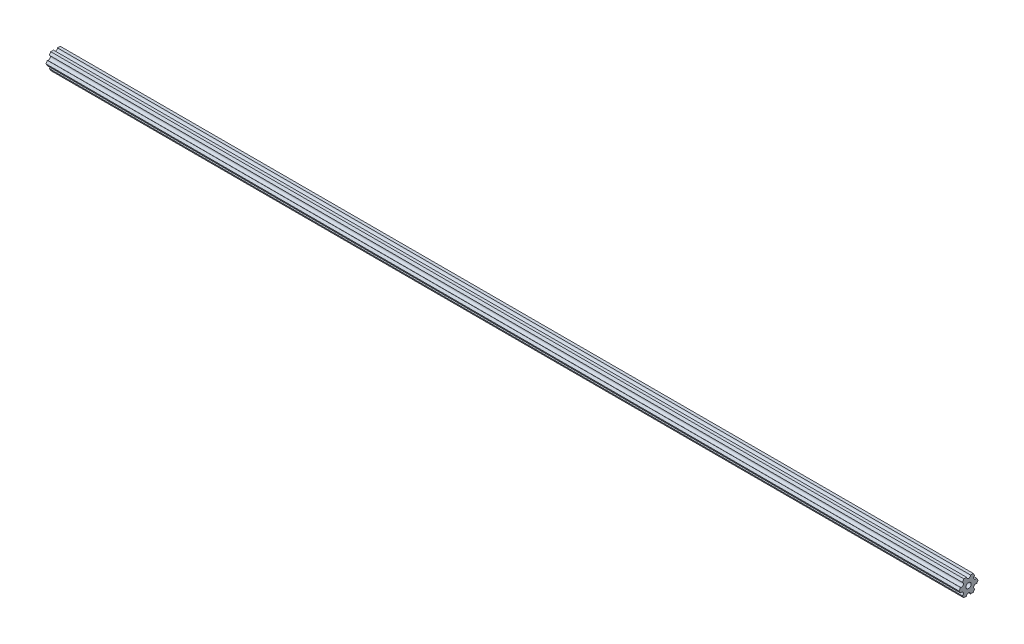
SolidWorks part; units mm, degrees
material "6061 Alloy"
ref_plane "Front Plane" through (0, 0, 0) normal (0, 0, 1) x (1, 0, 0)
ref_plane "Top Plane" through (0, 0, 0) normal (0, 1, 0) x (1, 0, 0)
ref_plane "Right Plane" through (0, 0, 0) normal (1, 0, 0) x (0, 0, -1)
sketch "Sketch1" plane through (0, 0, 0) normal (1, 0, 0) x (0, 0, -1)
  line L1 (7.3323, 0) -> (3.6662, 6.35)
  line L2 (3.6662, 6.35) -> (-3.6662, 6.35)
  line L3 (-3.6662, 6.35) -> (-7.3323, 0)
  line L4 (-7.3323, 0) -> (-3.6662, -6.35)
  line L5 (-3.6662, -6.35) -> (3.6662, -6.35)
  line L6 (3.6662, -6.35) -> (7.3323, 0)
  circle A0 centre (0, 0) radius 6.35 construction
  circle A1 centre (0, 0) radius 2.0193
  dimension "D1" = 12.7
  dimension "D2" = 4.0386
extrude "Boss-Extrude1" add sketch "Sketch1" along normal blind 714.375
sketch "Sketch2" plane through (714.375, 0, 0) normal (1, 0, 0) x (0, 0, -1)
  line L0 (3.6662, 6.35) -> (-3.6662, 6.35) construction
  line L1 (-3.6662, -6.35) -> (3.6662, -6.35) construction
  circle A0 centre (0, 6.35) radius 1.524
  circle A1 centre (5.4993, 3.175) radius 1.524
  circle A2 centre (5.4993, -3.175) radius 1.524
  circle A3 centre (0, -6.35) radius 1.524
  circle A4 centre (-5.4993, -3.175) radius 1.524
  circle A5 centre (-5.4993, 3.175) radius 1.524
  point P16 (0, 0)
  dimension "D1" = 3.048
  dimension "D2" = 6
extrude "Cut-Extrude1" cut sketch "Sketch2" against normal through all
sketch "Sketch3" plane through (714.375, 0, 0) normal (1, 0, 0) x (0, 0, -1)
  circle A0 centre (0, 0) radius 21.256
extrude "Cut-Extrude2" cut sketch "Sketch3" against normal blind 6.35
